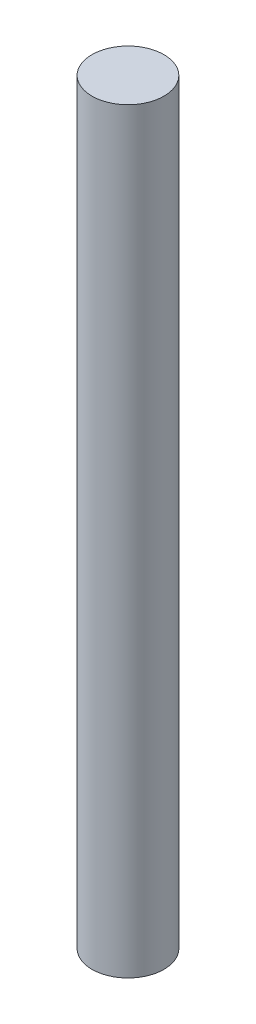
SolidWorks part; units mm, degrees
ref_plane "Front Plane" through (0, 0, 0) normal (0, 0, 1) x (1, 0, 0)
ref_plane "Top Plane" through (0, 0, 0) normal (0, 1, 0) x (1, 0, 0)
ref_plane "Right Plane" through (0, 0, 0) normal (1, 0, 0) x (0, 0, -1)
sketch "Sketch1" plane through (0, 0, 0) normal (0, 1, 0) x (1, 0, 0)
  circle A0 centre (0, 0) radius 1
  dimension "D1" = 2
extrude "Boss-Extrude1" add sketch "Sketch1" along normal blind 21.02
